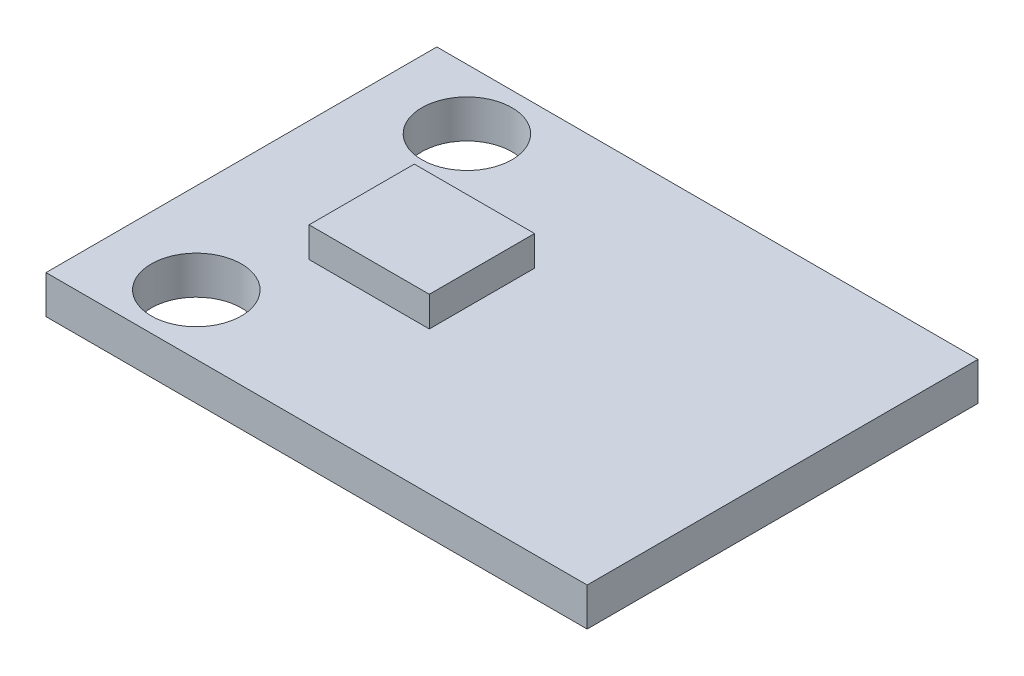
SolidWorks part; units mm, degrees
ref_plane "Front Plane" through (0, 0, 0) normal (0, 0, 1) x (1, 0, 0)
ref_plane "Top Plane" through (0, 0, 0) normal (0, 1, 0) x (1, 0, 0)
ref_plane "Right Plane" through (0, 0, 0) normal (1, 0, 0) x (0, 0, -1)
sketch "Sketch1" plane through (0, 0, 0) normal (0, 1, 0) x (1, 0, 0)
  line L1 (9, -6.5) -> (-9, -6.5)
  line L2 (9, -6.5) -> (9, 6.5)
  line L3 (9, 6.5) -> (-9, 6.5)
  line L4 (-9, -6.5) -> (-9, 6.5)
  line L5 (9, -6.5) -> (-9, 6.5) construction
  line L6 (9, 6.5) -> (-9, -6.5) construction
  point P0 (0, 0)
  dimension "D1" = 18
  dimension "D2" = 13
extrude "Boss-Extrude1" add sketch "Sketch1" along normal blind 1.27
sketch "Sketch2" plane through (0, 1.27, 0) normal (0, 1, 0) x (1, 0, 0)
  line L0 (-9, 6.5) -> (-9, -6.5) construction
  line L1 (9, 6.5) -> (-9, 6.5) construction
  circle A0 centre (-6, 4.5) radius 1.5
  dimension "D3" = 3
  dimension "D1" = 3
  dimension "D2" = 2
extrude "Cut-Extrude1" cut sketch "Sketch2" against normal up to next
sketch "Sketch3" plane through (0, 1.27, 0) normal (0, 1, 0) x (1, 0, 0)
  line L2 (-9, -6.5) -> (9, -6.5) construction
  line L3 (-9, 6.5) -> (-9, -6.5) construction
  circle A0 centre (-6, -4.5) radius 1.5
  dimension "D3" = 3
  dimension "D1" = 2
  dimension "D2" = 3
extrude "Cut-Extrude2" cut sketch "Sketch3" against normal up to next
sketch "Sketch4" plane through (0, 1.27, 0) normal (0, 1, 0) x (1, 0, 0)
  line L0 (-9, 6.5) -> (-9, -6.5) construction
  line L1 (-5, 1.75) -> (-1, 1.75)
  line L2 (-5, 1.75) -> (-5, -1.75)
  line L3 (-5, -1.75) -> (-1, -1.75)
  line L4 (-1, 1.75) -> (-1, -1.75)
  line L5 (9, 6.5) -> (-9, 6.5) construction
  line L6 (9, -6.5) -> (9, 6.5) construction
  dimension "D1" = 4
  dimension "D2" = 3.5
  dimension "D3" = 8
  dimension "D4" = 4.75
  dimension "D5" = 10
extrude "Boss-Extrude2" add sketch "Sketch4" along normal blind 1
